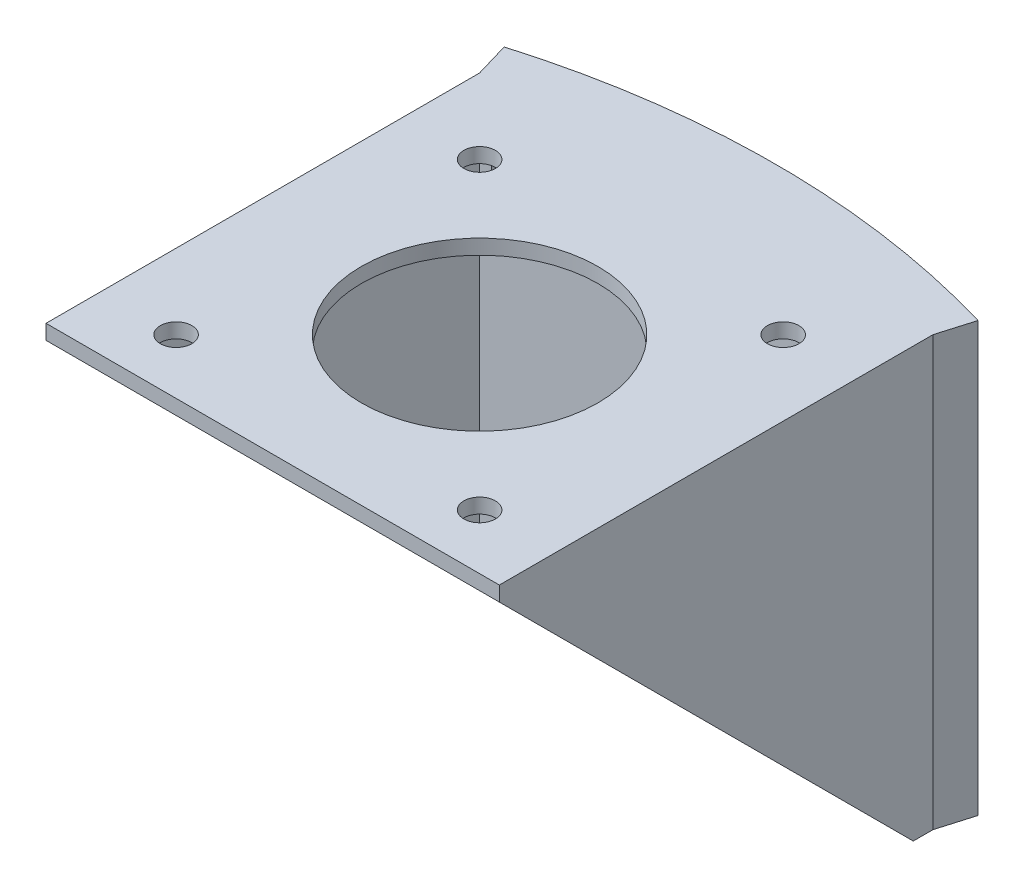
SolidWorks part; units mm, degrees
ref_plane "Front Plane" through (0, 0, 0) normal (0, 0, 1) x (1, 0, 0)
ref_plane "Top Plane" through (0, 0, 0) normal (0, 1, 0) x (1, 0, 0)
ref_plane "Right Plane" through (0, 0, 0) normal (1, 0, 0) x (0, 0, -1)
sketch "Sketch4" plane through (0, 0, 0) normal (0, 1, 0) x (1, 0, 0)
  line L0 (0, 21) -> (0, -21) construction
  line L1 (-21, -21) -> (21, -21)
  line L2 (-21, -21) -> (-21, 21)
  line L3 (-21, 21) -> (21, 21)
  line L4 (21, -21) -> (21, 21)
  line L5 (-21, -21) -> (21, 21) construction
  line L6 (-21, 21) -> (21, -21) construction
  line L7 (-21, 0) -> (21, 0) construction
  circle A0 centre (-15.4, 15.4) radius 1.6
  circle A1 centre (15.4, 15.4) radius 1.6
  circle A2 centre (15.4, -15.4) radius 1.6
  circle A3 centre (-15.4, -15.4) radius 1.6
  point P0 (0, 0)
  dimension "D3" = 3.2
  dimension "D1" = 42
  dimension "D2" = 42
  dimension "D4" = 4
extrude "Boss-Extrude1" add sketch "Sketch4" along normal blind 1.5
sketch "Sketch5" plane through (0, 1.5, 0) normal (0, 1, 0) x (1, 0, 0)
  circle A0 centre (0, 0) radius 12
extrude "Cut-Extrude1" cut sketch "Sketch5" against normal through all
sketch "Sketch6" plane through (21, 0, 0) normal (1, 0, 0) x (0, 0, -1)
  line L0 (-21, 0) -> (21, -42)
  line L1 (21, -42) -> (21, 0)
  line L3 (-21, 0) -> (-21, 1.5)
  line L4 (-21, 1.5) -> (21, 1.5)
  line L5 (21, 1.5) -> (21, 0)
  line L6 (-21, 0) -> (21, 0) construction
  dimension "D1" = 45
extrude "Boss-Extrude2" add sketch "Sketch6" along normal blind 2 contours L1 L5 L4 L3 L0
mirror "Mirror1" about plane through (0, 0, 0) normal (1, 0, 0) of "Boss-Extrude2"
sketch "Sketch7" plane through (0, 0, -21) normal (0, 0, -1) x (-1, 0, 0)
  line L1 (-23, 1.5) -> (23, 1.5)
  line L2 (-23, 1.5) -> (-23, -42)
  line L3 (-23, -42) -> (23, -42)
  line L4 (23, 1.5) -> (23, -42)
extrude "Boss-Extrude3" add sketch "Sketch7" along normal blind 2
sketch "Sketch8" plane through (-21, 0, 0) normal (1, 0, 0) x (0, 0, -1)
  line L0 (-21, 0) -> (21, -42)
  line L1 (21, -42) -> (21, 0)
  line L2 (21, 0) -> (-21, 0)
extrude "Cut-Extrude2" cut sketch "Sketch8" against normal blind 0.2
mirror "Mirror2" about plane through (0, 0, 0) normal (1, 0, 0) of "Cut-Extrude2"
sketch "Sketch9" plane through (0, 0, -21) normal (0, 0, 1) x (1, 0, 0)
  line L1 (-21.2, -42) -> (21.2, -42)
  line L2 (-21.2, -42) -> (-21.2, 0)
  line L3 (-21.2, 0) -> (21.2, 0)
  line L4 (21.2, -42) -> (21.2, 0)
extrude "Cut-Extrude3" cut sketch "Sketch9" against normal blind 0.2
sketch "Sketch10" plane through (0, 0, -21.2) normal (0, 0, 1) x (1, 0, 0)
  line L0 (0, 0) -> (0, -17.7317) construction
  line L1 (-5, -40) -> (5, -40)
  line L2 (-5, -40) -> (-5, -30)
  line L3 (-5, -30) -> (5, -30)
  line L4 (5, -40) -> (5, -30)
  line L5 (-5, -40) -> (5, -30) construction
  line L6 (-5, -30) -> (5, -40) construction
  line L7 (-21.2, -42) -> (21.2, -42) construction
  point P0 (0, -35)
  dimension "D1" = 10
  dimension "D2" = 10
  dimension "D3" = 0
  dimension "D4" = 2
sketch "Sketch12" plane through (0, 0, -21.2) normal (0, 0, 1) x (1, 0, 0)
  line L0 (0, 0) -> (0, -4.6) construction
  line L1 (16.4, -4.6) -> (0, -4.6) construction
  line L4 (16.4, 0) -> (16.4, -3) construction
  line L5 (21.2, 0) -> (-21.2, 0) construction
  circle A0 centre (16.4, -4.6) radius 1.6
  dimension "D3" = 3.2
  dimension "D1" = 3
  dimension "D2" = 16.4
sketch "Sketch14" plane through (0, 1.5, 0) normal (0, 1, 0) x (1, 0, 0)
  line L3 (-23, 23) -> (23, 23)
  line L8 (0, 0) -> (0, -55) construction
  line L9 (-23, 23) -> (-24.0407, 26.5294)
  line L10 (23, 23) -> (24.0407, 26.5294)
  arc A4 (24.0407, 26.5294) -> (-24.0407, 26.5294) centre (0, -55) ccw
  dimension "D1" = 170
  dimension "D2" = 55
extrude "Boss-Extrude4" add sketch "Sketch14" against normal up to surface (43.5 mm away) up to face at (0, -42, -21.55)
sketch "Sketch16" plane through (0, -42, 0) normal (0, -1, 0) x (1, 0, 0)
  line L0 (-5, -21.2) -> (5, -21.2) construction
  line L1 (5, -21.2) -> (-5, -21.2)
  line L2 (5, -21.2) -> (5, -26.2)
  line L3 (5, -26.2) -> (-5, -26.2)
  line L4 (-5, -21.2) -> (-5, -26.2)
  line L5 (-5, -21.2) -> (5, -21.2) construction
  dimension "D1" = 5
extrude "Cut-Extrude6" cut sketch "Sketch16" against normal blind 12
extrude "Cut-Extrude8" cut sketch "Sketch12" against normal through all
sketch "Sketch18" plane through (0, 0, -21.2) normal (0, 0, 1) x (1, 0, 0)
  circle A0 centre (16.4, -4.6) radius 3.6
extrude "Cut-Extrude9" cut sketch "Sketch18" against normal blind 1.5
sketch "Sketch19" plane through (0, 0, -21.2) normal (0, 0, 1) x (1, 0, 0)
  line L0 (-21.2, -21) -> (21.2, -21) construction
  line L1 (-21.2, 0) -> (-21.2, -42) construction
  line L2 (21.2, 0) -> (21.2, -42) construction
  line L3 (0, 0) -> (0, -30) construction
  line L4 (5, -30) -> (-5, -30) construction
sketch "Sketch20" plane through (-21.2, 0, 0) normal (1, 0, 0) x (0, 0, -1)
  line L0 (21.2, -21) -> (0, -21) construction
  line L1 (-21, 0) -> (21, -42) construction
sketch "Sketch21" plane through (0, 0, 0) normal (0, -1, 0) x (1, 0, 0)
  line L0 (0, -21.2) -> (0, -12) construction
  line L1 (-21.2, -21.2) -> (21.2, -21.2) construction
  circle A0 centre (0, 0) radius 12 construction
ref_plane "Plane1" through (0, 0, 0) normal (1, 0, 0) x (0, 0, -1)
ref_plane "Plane2" through (0, -21, 0) normal (0, -1, 0) x (-1, 0, 0)
mirror "Mirror7" about plane through (0, -21, 0) normal (0, -1, 0) of "Cut-Extrude9" second plane through (0, 0, 0) second plane normal (1, 0, 0)
sketch "Sketch22" plane through (0, 0, -21.2) normal (0, 0, 1) x (1, 0, 0)
  circle A0 centre (-16.4, -37.4) radius 1.6
  circle A1 centre (-16.4, -4.6) radius 1.6
  circle A2 centre (16.4, -37.4) radius 1.6
  dimension "D1" = 3.2
  dimension "D2" = 3.2
  dimension "D3" = 3.2
extrude "Cut-Extrude10" cut sketch "Sketch22" against normal up to surface (7.5016 mm away)
